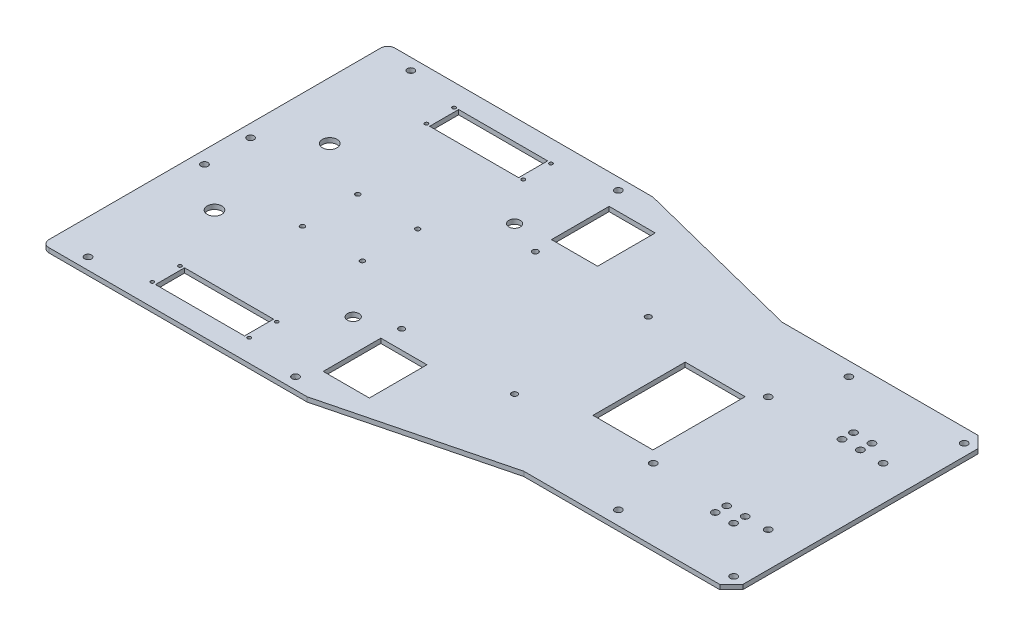
SolidWorks part; units mm, degrees
ref_plane "Alzado" through (0, 0, 0) normal (0, 0, 1) x (1, 0, 0)
ref_plane "Planta" through (0, 0, 0) normal (0, 1, 0) x (1, 0, 0)
ref_plane "Vista lateral" through (0, 0, 0) normal (1, 0, 0) x (0, 0, -1)
sketch "Croquis base" plane through (0, 0, 0) normal (0, 1, 0) x (1, 0, 0)
  line L0 (50, 75) -> (50, -75) construction
  line L1 (-140, 75) -> (-25, 75)
  line L2 (-140, 75) -> (-140, -75)
  line L3 (-140, -75) -> (-25, -75)
  line L4 (140, 56) -> (140, -56)
  line L5 (-25, 75) -> (-25, -75) construction
  line L6 (50, 56) -> (140, 56)
  line L7 (50, -56) -> (140, -56)
  line L8 (50, 56) -> (-25, 75)
  line L9 (-25, -75) -> (50, -56)
  point P0 (0, 0)
  dimension "D1" = 280
  dimension "D2" = 150
  dimension "D3" = 90
  dimension "D4" = 75
  dimension "D5" = 19
  dimension "D6" = 19
extrude "Saliente-Extruir1" add sketch "Croquis base" along normal blind 2
sketch "Croquis barrenos" plane through (0, 2, 0) normal (0, 1, 0) x (1, 0, 0)
  line L0 (-140, 70) -> (-15.6386, 70) construction
  line L1 (-140, 75) -> (-140, -75) construction
  line L2 (-140, -70) -> (-15.6386, -70) construction
  line L3 (-125, 75) -> (-125, -75) construction
  line L4 (-25, 75) -> (-140, 75) construction
  line L5 (-140, -75) -> (-25, -75) construction
  line L6 (-35, 75) -> (-35, -75) construction
  line L7 (140, 50) -> (42.5717, 50) construction
  line L8 (140, -56) -> (140, 56) construction
  line L9 (140, -50) -> (42.5717, -50) construction
  line L10 (135, 56) -> (135, -56) construction
  line L11 (140, 56) -> (50, 56) construction
  line L12 (50, -56) -> (140, -56) construction
  line L13 (85, 56) -> (85, -56) construction
  line L14 (-140, 0) -> (140, 0) construction
  line L15 (-100, -53.146) -> (-61.4, -53.146)
  line L16 (-100, -53.146) -> (-100, -65.746)
  line L17 (-100, -65.746) -> (-61.4, -65.746)
  line L18 (-61.4, -53.146) -> (-61.4, -65.746)
  line L19 (-100, -53.146) -> (-61.4, -65.746) construction
  line L20 (-100, -65.746) -> (-61.4, -53.146) construction
  line L21 (-31, -37) -> (-11, -37)
  line L22 (-31, -37) -> (-31, -62)
  line L23 (-31, -62) -> (-11, -62)
  line L24 (-11, -37) -> (-11, -62)
  line L25 (-31, -37) -> (-11, -62) construction
  line L26 (-31, -62) -> (-11, -37) construction
  line L27 (44, 20) -> (44, -20)
  line L28 (70, 20) -> (70, -20)
  line L29 (70, -20) -> (44, -20)
  line L30 (70, 20) -> (44, 20)
  line L31 (-101.7, -53.446) -> (-59.7, -53.446) construction
  line L32 (-101.7, -53.446) -> (-101.7, -65.446) construction
  line L33 (-101.7, -65.446) -> (-59.7, -65.446) construction
  line L34 (-59.7, -53.446) -> (-59.7, -65.446) construction
  line L35 (-101.7, -53.446) -> (-59.7, -65.446) construction
  line L36 (-101.7, -65.446) -> (-59.7, -53.446) construction
  line L37 (-100, 53.146) -> (-61.4, 53.146)
  line L38 (-100, 53.146) -> (-100, 65.746)
  line L39 (-100, 65.746) -> (-61.4, 65.746)
  line L40 (-61.4, 53.146) -> (-61.4, 65.746)
  line L41 (-31, 37) -> (-11, 37)
  line L42 (-31, 37) -> (-31, 62)
  line L43 (-31, 62) -> (-11, 62)
  line L44 (-11, 37) -> (-11, 62)
  line L45 (124.926, -24.926) -> (100.001, 0) construction
  circle A0 centre (-125, -70) radius 1.5
  circle A1 centre (-35, -70) radius 1.5
  circle A2 centre (85, -50) radius 1.5
  circle A3 centre (135, -50) radius 1.5
  circle A4 centre (-134.5, -10) radius 1.5
  circle A5 centre (-90, -12) radius 1
  circle A6 centre (-64, -12) radius 1
  circle A7 centre (-101.7, -53.446) radius 0.75
  circle A8 centre (-101.7, -65.446) radius 0.75
  circle A9 centre (-59.7, -53.446) radius 0.75
  circle A10 centre (-59.7, -65.446) radius 0.75
  circle A11 centre (-30, -29) radius 1.25
  circle A12 centre (19, -29) radius 1.25
  circle A13 centre (75.0759, -24.926) radius 1.5
  circle A14 centre (124.926, -24.926) radius 1.5
  circle A15 centre (107, -25) radius 1.5
  circle A16 centre (115, -25) radius 1.5
  circle A17 centre (115, -30) radius 1.5
  circle A19 centre (107, -30) radius 1.5
  circle A20 centre (-45, -35) radius 2.5
  circle A21 centre (-115.161, -25) radius 3.172
  circle A22 centre (135, 50) radius 1.5
  circle A23 centre (85, 50) radius 1.5
  circle A24 centre (124.926, 24.926) radius 1.5
  circle A25 centre (115, 30) radius 1.5
  circle A26 centre (115, 25) radius 1.5
  circle A27 centre (107, 25) radius 1.5
  circle A28 centre (107, 30) radius 1.5
  circle A29 centre (75.0759, 24.926) radius 1.5
  circle A30 centre (-90, 12) radius 1
  circle A31 centre (-59.7, 65.446) radius 0.75
  circle A32 centre (-59.7, 53.446) radius 0.75
  circle A33 centre (-101.7, 53.446) radius 0.75
  circle A34 centre (-101.7, 65.446) radius 0.75
  circle A35 centre (19, 29) radius 1.25
  circle A36 centre (-30, 29) radius 1.25
  circle A37 centre (-64, 12) radius 1
  circle A38 centre (-45, 35) radius 2.5
  circle A39 centre (-35, 70) radius 1.5
  circle A40 centre (-125, 70) radius 1.5
  circle A41 centre (-115.161, 25) radius 3.172
  circle A42 centre (-134.5, 10) radius 1.5
  arc A43 (74.0381, -23.843) -> (125.9639, -23.843) centre (100.001, 0) ccw construction
  arc A44 (125.9639, 23.843) -> (74.0381, 23.843) centre (100.001, 0) ccw construction
  point P28 (-80.7, -59.446)
  point P33 (-21, -49.5)
  point P58 (-80.7, -59.446)
  point P104 (70, 0)
  point P105 (44, 0)
  point P141 (0, 0)
  point P142 (0, 0)
  dimension "D20" = 3
  dimension "D26" = 2
  dimension "D29" = 1.5
  dimension "D33" = 2.5
  dimension "D43" = 3
  dimension "D46" = 5
  dimension "D48" = 6.344
  dimension "D1" = 15
  dimension "D2" = 5
  dimension "D3" = 5
  dimension "D4" = 90
  dimension "D5" = 6
  dimension "D6" = 6
  dimension "D7" = 5
  dimension "D8" = 50
  dimension "D9" = 38.6
  dimension "D10" = 12.6
  dimension "D11" = 59.3
  dimension "D12" = 15.554
  dimension "D13" = 25
  dimension "D14" = 20
  dimension "D15" = 119
  dimension "D16" = 25.5
  dimension "D17" = 26
  dimension "D18" = 20
  dimension "D19" = 184
  dimension "D21" = 5.5
  dimension "D22" = 65
  dimension "D23" = 50
  dimension "D24" = 63
  dimension "D25" = 26
  dimension "D27" = 1.7
  dimension "D28" = 0.3
  dimension "D30" = 49
  dimension "D31" = 46
  dimension "D32" = 5
  dimension "D35" = 15.074
  dimension "D36" = 31.074
  dimension "D37" = 8
  dimension "D38" = 5
  dimension "D39" = 25
  dimension "D40" = 8
  dimension "D41" = 5
  dimension "D42" = 26
  dimension "D44" = 95
  dimension "D45" = 40
  dimension "D47" = 25
  dimension "D49" = 24.839
  dimension "D50" = 35.25
extrude "Cortar-Extruir1" cut sketch "Croquis barrenos" against normal through all
fillet "Redondeo1" radius 3 2 edges at (-140, 1, -75) (-140, 1, 75)
chamfer "Chaflán2" distance 5 angle 45 2 edges at (140, 1, -56) (140, 1, 56)
